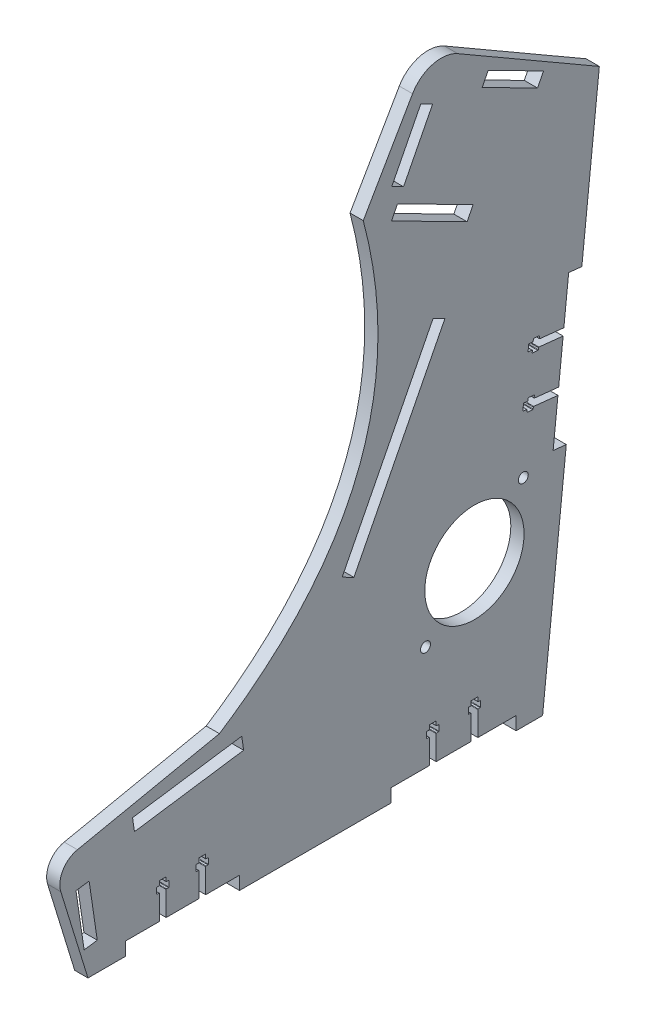
SolidWorks part; units mm, degrees
ref_plane "Front Plane" through (0, 0, 0) normal (0, 0, 1) x (1, 0, 0)
ref_plane "Top Plane" through (0, 0, 0) normal (0, 1, 0) x (1, 0, 0)
ref_plane "Right Plane" through (0, 0, 0) normal (1, 0, 0) x (0, 0, -1)
sketch "Sketch5" plane through (0, 0, 0) normal (1, 0, 0) x (0, 0, -1)
  line L0 (200.2204, 680.0165) -> (997.5537, 680.0165) construction
  line L1 (0, 0) -> (500, 0)
  dimension "D1" = 500
sketch "Sketch6" plane through (0, 0, 0) normal (1, 0, 0) x (0, 0, -1)
  line L0 (443.0084, 0) -> (494.424, 483.6515)
  line L2 (494.424, 483.6515) -> (366.15, 557.8015)
  line L3 (325.1634, 546.8425) -> (280.507, 469.5903)
  line L5 (150.1347, 132.2032) -> (21.4929, 105.4355)
  line L7 (6.4499, 79.9789) -> (31.0328, 0)
  line L8 (31.0328, 0) -> (443.0084, 0)
  arc A0 (366.15, 557.8015) -> (325.1634, 546.8425) centre (351.1362, 531.8287) ccw
  arc A1 (21.4929, 105.4355) -> (6.4499, 79.9789) centre (25.5672, 85.8549) ccw
  spline S0 degree 2 poles (280.507, 469.5903) (337.5474, 253.6662) (150.1347, 132.2032) knots 0 0 0 1 1 1
  point P15 (0, 100.9633)
  dimension "D1" = 30
  dimension "D2" = 20
  dimension "D3" = 411.9756
  dimension "D4" = 486.3768
  dimension "D5" = 131.3972
  dimension "D6" = 89.2306
  dimension "D7" = 148.1635
  dimension "D8" = 83.6716
extrude "Boss-Extrude3" add sketch "Sketch6" along normal blind 12
sketch "Sketch7" plane through (12, 0, 0) normal (1, 0, 0) x (0, 0, -1)
  line L0 (27.5611, 23.7476) -> (16.7625, 97.6133)
  line L1 (16.7625, 97.6133) -> (225.0412, 128.062)
  line L2 (225.0412, 128.062) -> (374.5816, 421.6774)
  line L3 (374.5816, 421.6774) -> (295.4085, 462.0008)
  line L4 (295.4085, 462.0008) -> (343.5234, 556.4723)
  line L5 (343.5234, 556.4723) -> (443.8491, 505.3757)
  line L6 (443.8491, 505.3757) -> (438.403, 494.6827)
  line L7 (438.403, 494.6827) -> (348.7704, 540.3332)
  line L8 (348.7704, 540.3332) -> (311.5475, 467.2478)
  line L9 (311.5475, 467.2478) -> (390.7206, 426.9244)
  line L10 (390.7206, 426.9244) -> (232.9177, 117.086)
  line L11 (232.9177, 117.086) -> (30.3721, 87.4754)
  line L12 (30.3721, 87.4754) -> (39.4349, 25.4834)
  line L14 (39.4349, 25.4834) -> (27.5611, 23.7476)
  dimension "D1" = 12
  dimension "D2" = 12
  dimension "D3" = 12
  dimension "D4" = 12
  dimension "D5" = 12
  dimension "D6" = 12
  dimension "D7" = 74.6509
  dimension "D8" = 210.4926
  dimension "D9" = 347.7091
  dimension "D10" = 100.8502
  dimension "D11" = 106.0184
  dimension "D12" = 112.5881
  dimension "D13" = 341.5032
extrude "Cut-Extrude1" cut sketch "Sketch7" against normal through all
sketch "Sketch9" plane through (12, 0, 0) normal (1, 0, 0) x (0, 0, -1)
  line L0 (16.7625, 97.6133) -> (20.2342, 73.8657)
  line L1 (16.7625, 97.6133) -> (27.5611, 23.7476) construction
  line L2 (20.2342, 73.8657) -> (32.108, 75.6016)
  line L3 (39.4349, 25.4834) -> (30.3721, 87.4754) construction
  line L4 (32.108, 75.6016) -> (28.6363, 99.3492)
  line L5 (225.0412, 128.062) -> (16.7625, 97.6133) construction
  line L6 (28.6363, 99.3492) -> (16.7625, 97.6133)
  dimension "D1" = 24
extrude "Boss-Extrude10" add sketch "Sketch9" against normal blind 12
sketch "Sketch10" plane through (12, 0, 0) normal (1, 0, 0) x (0, 0, -1)
  line L0 (28.6363, 99.3492) -> (71.4314, 105.6055)
  line L1 (225.0412, 128.062) -> (28.6363, 99.3492) construction
  line L2 (71.4314, 105.6055) -> (73.1672, 93.7317)
  line L3 (30.3721, 87.4754) -> (232.9177, 117.086) construction
  line L4 (73.1672, 93.7317) -> (30.3721, 87.4754)
  line L5 (30.3721, 87.4754) -> (28.6363, 99.3492)
  line L6 (225.0412, 128.062) -> (170.3723, 120.0699)
  line L7 (170.3723, 120.0699) -> (172.1081, 108.1961)
  line L8 (172.1081, 108.1961) -> (232.9177, 117.086)
  line L9 (232.9177, 117.086) -> (225.0412, 128.062)
  dimension "D1" = 43.25
  dimension "D2" = 55.25
extrude "Boss-Extrude11" add sketch "Sketch10" against normal blind 12
sketch "Sketch11" plane through (12, 0, 0) normal (1, 0, 0) x (0, 0, -1)
  line L0 (390.7206, 426.9244) -> (354.4137, 355.6376)
  line L1 (232.9177, 117.086) -> (390.7206, 426.9244) construction
  line L2 (354.4137, 355.6376) -> (343.7207, 361.0836)
  line L3 (374.5816, 421.6774) -> (225.0412, 128.062) construction
  line L4 (343.7207, 361.0836) -> (380.0276, 432.3705)
  line L5 (390.7206, 426.9244) -> (311.5475, 467.2478) construction
  line L6 (380.0276, 432.3705) -> (390.7206, 426.9244)
  line L7 (272.0425, 193.9056) -> (232.9177, 117.086)
  line L8 (232.9177, 117.086) -> (225.0412, 128.062)
  line L9 (225.0412, 128.062) -> (261.3495, 199.3517)
  line L10 (261.3495, 199.3517) -> (272.0425, 193.9056)
  dimension "D1" = 80
  dimension "D2" = 181.5
extrude "Boss-Extrude12" add sketch "Sketch11" against normal blind 12
sketch "Sketch12" plane through (12, 0, 0) normal (1, 0, 0) x (0, 0, -1)
  line L0 (295.4085, 462.0008) -> (306.3006, 483.3869)
  line L1 (343.5234, 556.4723) -> (295.4085, 462.0008) construction
  line L2 (306.3006, 483.3869) -> (316.9936, 477.9409)
  line L3 (311.5475, 467.2478) -> (348.7704, 540.3332) construction
  line L4 (316.9936, 477.9409) -> (306.1015, 456.5548)
  line L5 (295.4085, 462.0008) -> (374.5816, 421.6774) construction
  line L6 (306.1015, 456.5548) -> (295.4085, 462.0008)
  line L7 (343.5234, 556.4723) -> (332.6314, 535.0862)
  line L8 (332.6314, 535.0862) -> (343.3244, 529.6402)
  line L9 (343.3244, 529.6402) -> (348.7704, 540.3332)
  line L10 (348.7704, 540.3332) -> (388.2455, 520.2283)
  line L11 (348.7704, 540.3332) -> (438.403, 494.6827) construction
  line L12 (388.2455, 520.2283) -> (393.6915, 530.9213)
  line L13 (443.8491, 505.3757) -> (343.5234, 556.4723) construction
  line L14 (393.6915, 530.9213) -> (343.5234, 556.4723)
  dimension "D1" = 24
  dimension "D2" = 24
  dimension "D3" = 56.3
extrude "Boss-Extrude13" add sketch "Sketch12" against normal blind 12
sketch "Sketch13" plane through (12, 0, 0) normal (1, 0, 0) x (0, 0, -1)
  line L0 (0, 0) -> (500, 0) construction
  line L1 (419.0084, 0) -> (305.6784, 0)
  line L2 (419.0084, 0) -> (419.0084, 12)
  line L3 (419.0084, 12) -> (305.6784, 12)
  line L4 (305.6784, 0) -> (305.6784, 12)
  line L6 (65.0217, 0) -> (168.3517, 0)
  line L7 (65.0217, 0) -> (65.0217, 12)
  line L8 (65.0217, 12) -> (168.3517, 12)
  line L9 (168.3517, 0) -> (168.3517, 12)
  dimension "D1" = 12
  dimension "D2" = 12
  dimension "D3" = 113.33
  dimension "D4" = 24
  dimension "D5" = 137.3267
  dimension "D6" = 103.33
extrude "Cut-Extrude2" cut sketch "Sketch13" against normal blind 12
sketch "Sketch15" plane through (12, 0, 0) normal (1, 0, 0) x (0, 0, -1)
  line L0 (464.4724, 201.9057) -> (452.5396, 203.1743)
  line L1 (443.0084, 0) -> (494.424, 483.6515) construction
  line L2 (452.5396, 203.1743) -> (466.6345, 335.7605)
  line L3 (466.6345, 335.7605) -> (478.5673, 334.492)
  line L4 (478.5673, 334.492) -> (464.4724, 201.9057)
  dimension "D1" = 12
  dimension "D2" = 133.3333
  dimension "D3" = 150
extrude "Cut-Extrude4" cut sketch "Sketch15" against normal blind 12
scale "Scale1" scale about centroid uniform scaling yes scale factor 0.5
hole_wizard "M4 Clearance Slot1" positions "Sketch16" profile "Sketch17" size "M4" standard "ANSI Metric" slot yes end condition through all
sketch "Sketch16" plane through (3, 0, 0) normal (-1, 0, 0) x (0, 0, 1)
  point P0 (-371.8327, 207.0251)
  point P3 (-327.5327, 162.7251)
sketch "Sketch17" plane through (3, 207.0251, -371.8327) normal (0, 1, 0) x (0, 0, 1)
  line L0 (0, 0) -> (0, 6)
  line L1 (0, 6) -> (2.25, 6)
  line L2 (2.25, 6) -> (2.25, 0)
  line L5 (2.25, 0) -> (0, 0)
  line L11 (0, -6.35) -> (0, 107.95) construction
  dimension "Thru Hole Dia." = 4.5
  dimension "Thru Hole Depth" = 6
sketch "Sketch18" plane through (9, 0, 0) normal (1, 0, 0) x (0, 0, -1)
  circle A0 centre (349.6827, 184.8751) radius 22.5
  dimension "D1" = 45
extrude "Cut-Extrude5" cut sketch "Sketch18" against normal up to next
sketch "Sketch22" plane through (0, -38.1506, -358.8717) normal (0, -0.1057, -0.9944) x (-1, 0, 0)
  line L0 (-3, 317.1443) -> (-3, 250.4776) construction
  line L1 (-9, 293.3743) -> (-3, 293.3743)
  line L2 (-9, 293.3743) -> (-9, 296.4743)
  line L3 (-9, 296.4743) -> (-3, 296.4743)
  line L4 (-3, 293.3743) -> (-3, 296.4743)
  line L5 (-9, 293.3743) -> (-3, 296.4743) construction
  line L6 (-9, 296.4743) -> (-3, 293.3743) construction
  line L8 (-9, 271.1476) -> (-3, 271.1476)
  line L9 (-9, 271.1476) -> (-9, 274.2476)
  line L10 (-9, 274.2476) -> (-3, 274.2476)
  line L11 (-3, 271.1476) -> (-3, 274.2476)
  line L12 (-9, 271.1476) -> (-3, 274.2476) construction
  line L13 (-9, 274.2476) -> (-3, 271.1476) construction
  point P0 (-6, 294.9243)
  point P8 (-6, 272.6976)
  dimension "D1" = 3.1
  dimension "D2" = 3.1
extrude "Cut-Extrude6" cut sketch "Sketch22" against normal blind 16
sketch "Sketch23" plane through (0, 115.3364, 0) normal (0, -1, 0) x (1, 0, 0)
  line L0 (9, -368.5844) -> (9, -311.9194) construction
  line L1 (3, -348.146) -> (9, -348.146)
  line L2 (3, -348.146) -> (3, -351.246)
  line L3 (3, -351.246) -> (9, -351.246)
  line L4 (9, -348.146) -> (9, -351.246)
  line L5 (3, -348.146) -> (9, -351.246) construction
  line L6 (3, -351.246) -> (9, -348.146) construction
  line L7 (9, -243.256) -> (9, -191.591) construction
  line L8 (3, -329.256) -> (9, -329.256)
  line L9 (3, -329.256) -> (3, -332.356)
  line L10 (3, -332.356) -> (9, -332.356)
  line L11 (9, -329.256) -> (9, -332.356)
  line L12 (3, -329.256) -> (9, -332.356) construction
  line L13 (3, -332.356) -> (9, -329.256) construction
  line L14 (3, -224.8194) -> (9, -224.8194)
  line L15 (3, -224.8194) -> (3, -227.9194)
  line L16 (3, -227.9194) -> (9, -227.9194)
  line L17 (9, -224.8194) -> (9, -227.9194)
  line L18 (3, -224.8194) -> (9, -227.9194) construction
  line L19 (3, -227.9194) -> (9, -224.8194) construction
  line L21 (3, -206.9294) -> (9, -206.9294)
  line L22 (3, -206.9294) -> (3, -210.0294)
  line L23 (3, -210.0294) -> (9, -210.0294)
  line L24 (9, -206.9294) -> (9, -210.0294)
  line L25 (3, -206.9294) -> (9, -210.0294) construction
  line L26 (3, -210.0294) -> (9, -206.9294) construction
  point P0 (6, -349.696)
  point P8 (6, -330.806)
  point P14 (6, -226.3694)
  point P22 (6, -208.4794)
  dimension "D1" = 3.1
  dimension "D2" = 3.1
  dimension "D3" = 3.1
  dimension "D4" = 3.1
extrude "Cut-Extrude7" cut sketch "Sketch23" against normal blind 16
sketch "Sketch24" plane through (9, 0, 0) normal (1, 0, 0) x (0, 0, -1)
  line L0 (371.9524, 236.2517) -> (371.6247, 233.1691) construction
  line L1 (346.946, 126.5364) -> (352.446, 126.5364)
  line L2 (346.946, 126.5364) -> (346.946, 129.3364)
  line L3 (346.946, 129.3364) -> (352.446, 129.3364)
  line L4 (352.446, 126.5364) -> (352.446, 129.3364)
  line L5 (346.946, 126.5364) -> (352.446, 129.3364) construction
  line L6 (346.946, 129.3364) -> (352.446, 126.5364) construction
  line L8 (374.302, 258.3539) -> (373.9743, 255.2712) construction
  line L9 (328.056, 126.5364) -> (333.556, 126.5364)
  line L10 (328.056, 126.5364) -> (328.056, 129.3364)
  line L11 (328.056, 129.3364) -> (333.556, 129.3364)
  line L12 (333.556, 126.5364) -> (333.556, 129.3364)
  line L13 (328.056, 126.5364) -> (333.556, 129.3364) construction
  line L14 (328.056, 129.3364) -> (333.556, 126.5364) construction
  line L15 (223.6194, 126.5364) -> (229.1194, 126.5364)
  line L16 (223.6194, 126.5364) -> (223.6194, 129.3364)
  line L17 (223.6194, 129.3364) -> (229.1194, 129.3364)
  line L18 (229.1194, 126.5364) -> (229.1194, 129.3364)
  line L19 (223.6194, 126.5364) -> (229.1194, 129.3364) construction
  line L20 (223.6194, 129.3364) -> (229.1194, 126.5364) construction
  line L21 (205.7294, 126.5364) -> (211.2294, 126.5364)
  line L22 (205.7294, 126.5364) -> (205.7294, 129.3364)
  line L23 (205.7294, 129.3364) -> (211.2294, 129.3364)
  line L24 (211.2294, 126.5364) -> (211.2294, 129.3364)
  line L25 (205.7294, 126.5364) -> (211.2294, 129.3364) construction
  line L26 (205.7294, 129.3364) -> (211.2294, 126.5364) construction
  line L28 (373.4919, 231.8141) -> (376.2762, 231.5181)
  line L29 (373.4919, 231.8141) -> (374.0733, 237.2833)
  line L30 (376.423, 259.3854) -> (379.2073, 259.0895)
  line L31 (376.423, 259.3854) -> (375.8415, 253.9163)
  line L32 (375.8415, 253.9163) -> (378.6259, 253.6203)
  line L33 (379.2073, 259.0895) -> (378.6259, 253.6203)
  line L34 (376.423, 259.3854) -> (378.6259, 253.6203) construction
  line L35 (374.0733, 237.2833) -> (376.8577, 236.9873)
  line L36 (375.8415, 253.9163) -> (379.2073, 259.0895) construction
  line L38 (374.302, 258.3539) -> (390.2124, 256.6625) construction
  line L39 (371.9524, 236.2517) -> (387.8628, 234.5604) construction
  line L40 (351.246, 131.3364) -> (348.146, 131.3364) construction
  line L41 (332.356, 131.3364) -> (329.256, 131.3364) construction
  line L42 (376.2762, 231.5181) -> (376.8577, 236.9873)
  line L43 (329.256, 131.3364) -> (332.356, 131.3364) construction
  line L44 (348.146, 131.3364) -> (351.246, 131.3364) construction
  line L45 (224.8194, 131.3364) -> (227.9194, 131.3364) construction
  line L46 (206.9294, 131.3364) -> (210.0294, 131.3364) construction
  line L47 (373.4919, 231.8141) -> (376.8577, 236.9873) construction
  line L50 (227.9194, 131.3364) -> (224.8194, 131.3364) construction
  line L51 (374.0733, 237.2833) -> (376.2762, 231.5181) construction
  line L52 (210.0294, 131.3364) -> (206.9294, 131.3364) construction
  point P0 (349.696, 127.9364)
  point P5 (330.806, 127.9364)
  point P7 (375.1748, 234.4007)
  point P12 (208.4794, 127.9364)
  point P13 (330.806, 129.3364)
  point P14 (226.3694, 127.9364)
  point P25 (208.4794, 131.3364)
  point P26 (377.5244, 256.5029)
  point P28 (330.806, 131.3364)
  point P49 (349.696, 131.3364)
  point P52 (226.3694, 131.3364)
  dimension "D1" = 2.8
  dimension "D2" = 5.5
  dimension "D3" = 2.8
  dimension "D4" = 2.8
  dimension "D5" = 5.5
  dimension "D6" = 2.8
  dimension "D7" = 2.8
  dimension "D8" = 5.5
  dimension "D9" = 5.5
  dimension "D10" = 5.5
  dimension "D11" = 2
  dimension "D12" = 2
  dimension "D13" = 1.25
  dimension "D14" = 1.25
  dimension "D15" = 2.8
  dimension "D16" = 2
  dimension "D17" = 2
  dimension "D18" = 5.5
  dimension "D19" = 2
  dimension "D20" = 2
extrude "Cut-Extrude8" cut sketch "Sketch24" against normal up to next
fillet "Fillet1" radius 0.2 60 edges at (6, 129.3364, -211.2294) (6, 129.3364, -205.7294) (6, 126.5364, -205.7294) (6, 126.5364, -206.9294) (6, 126.5364, -211.2294) (6, 126.5364, -210.0294) (6, 126.5364, -229.1194) (6, 126.5364, -227.9194) (6, 126.5364, -224.8194) (6, 126.5364, -223.6194) (6, 129.3364, -223.6194) (6, 129.3364, -229.1194) (6, 129.3364, -333.556) (6, 129.3364, -328.056) (6, 126.5364, -328.056) (6, 126.5364, -329.256) (6, 126.5364, -333.556) (6, 126.5364, -332.356) (6, 126.5364, -352.446) (6, 129.3364, -352.446) (6, 129.3364, -346.946) (6, 126.5364, -351.246) (6, 126.5364, -346.946) (6, 126.5364, -348.146) (6, 129.3364, -210.0294) (6, 131.3364, -210.0294) (6, 129.3364, -206.9294) (6, 131.3364, -206.9294) (6, 131.3364, -224.8194) (6, 129.3364, -224.8194) (6, 131.3364, -227.9194) (6, 129.3364, -227.9194) (6, 129.3364, -329.256) (6, 129.3364, -332.356) (6, 129.3364, -348.146) (6, 129.3364, -351.246) (6, 131.3364, -351.246) (6, 131.3364, -348.146) (6, 131.3364, -329.256) (6, 131.3364, -332.356) (6, 259.0895, -379.2073) (6, 236.9873, -376.8577) (6, 231.5181, -376.2762) (6, 254.7638, -378.7474) (6, 253.6203, -378.6259) (6, 253.9163, -375.8415) (6, 255.2712, -373.9743) (6, 232.6617, -376.3978) (6, 231.8141, -373.4919) (6, 233.1691, -371.6247) (6, 232.9577, -373.6135) (6, 236.2517, -371.9524) (6, 236.0403, -373.9412) (6, 237.2833, -374.0733) (6, 235.7443, -376.7255) (6, 255.0598, -375.9631) (6, 257.8465, -379.0751) (6, 258.3539, -374.302) (6, 259.3854, -376.423) (6, 258.1424, -376.2908)
